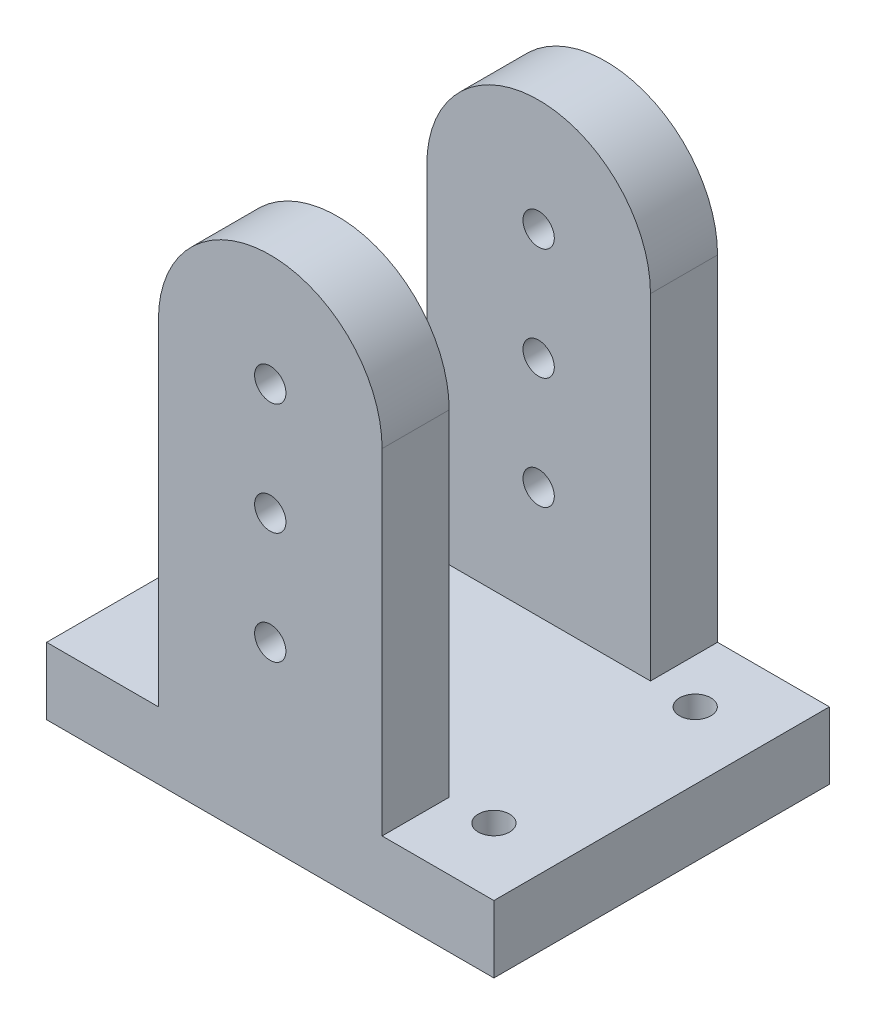
SolidWorks part; units mm, degrees
ref_plane "Front Plane" through (0, 0, 0) normal (0, 0, 1) x (1, 0, 0)
ref_plane "Top Plane" through (0, 0, 0) normal (0, 1, 0) x (1, 0, 0)
ref_plane "Right Plane" through (0, 0, 0) normal (1, 0, 0) x (0, 0, -1)
sketch "Sketch3" plane through (0, 0, 0) normal (0, 0, 1) x (1, 0, 0)
  line L0 (12.7, -38.1) -> (25.4, -38.1)
  line L1 (0, 1.778) -> (0, -1.778) construction
  line L2 (-12.7, 0) -> (-12.7, -38.1)
  line L4 (12.7, 0) -> (12.7, -38.1)
  line L5 (-25.4, -38.1) -> (-12.7, -38.1)
  line L6 (-25.4, -38.1) -> (-25.4, -45.72)
  line L7 (-25.4, -45.72) -> (25.4, -45.72)
  line L8 (25.4, -38.1) -> (25.4, -45.72)
  arc A0 (12.7, 0) -> (-12.7, 0) centre (0, 0) ccw
  circle A1 centre (0, 0) radius 1.778
  circle A2 centre (0, -12.7) radius 1.778
  circle A3 centre (0, -25.4) radius 1.778
  dimension "D1" = 25.4
  dimension "D6" = 3.556
  dimension "D9" = 3.556
  dimension "D10" = 3.556
  dimension "D2" = 50.8
  dimension "D3" = 25.4
  dimension "D4" = 7.62
  dimension "D5" = 38.1
  dimension "D7" = 12.7
  dimension "D8" = 12.7
extrude "Boss-Extrude2" add sketch "Sketch3" along normal blind 38.1
ref_plane "Plane1" through (0, 0, 19.05) normal (0, 0, 1) x (1, 0, 0)
sketch "Sketch8" plane through (0, 0, 0) normal (0, 1, 0) x (1, 0, 0)
  line L0 (-25.4, -38.1) -> (-25.4, 0) construction
  line L3 (25.4, 0) -> (12.7, 0) construction
  line L4 (25.4, -38.1) -> (25.4, 0) construction
  line L5 (25.4, -38.1) -> (12.7, -38.1) construction
  circle A0 centre (-17.78, -7.62) radius 1.778
  circle A1 centre (17.78, -7.62) radius 1.778
  circle A2 centre (17.78, -30.48) radius 1.778
  circle A3 centre (-17.78, -30.48) radius 1.778
  dimension "D9" = 3.556
  dimension "D10" = 3.556
  dimension "D11" = 3.556
  dimension "D12" = 3.556
  dimension "D1" = 7.62
  dimension "D2" = 7.62
  dimension "D3" = 7.62
  dimension "D4" = 7.62
  dimension "D5" = 7.62
  dimension "D6" = 7.62
  dimension "D7" = 7.62
  dimension "D8" = 7.62
sketch "Sketch11" plane through (0, 0, 0) normal (1, 0, 0) x (0, 0, -1)
  line L0 (-38.1, -38.1) -> (0, -38.1) construction
  line L1 (-30.48, -38.1) -> (-7.62, -38.1)
  line L2 (-30.48, -38.1) -> (-30.48, 12.7)
  line L3 (-30.48, 12.7) -> (-7.62, 12.7)
  line L4 (-7.62, -38.1) -> (-7.62, 12.7)
  line L5 (0, 12.7) -> (-38.1, 12.7) construction
  line L6 (-38.1, -38.1) -> (-38.1, 0) construction
  dimension "D1" = 22.86
  dimension "D2" = 7.62
extrude "Cut-Extrude3" cut sketch "Sketch11" against normal through all both and the other way through all
extrude "Cut-Extrude4" cut sketch "Sketch8" against normal through all
